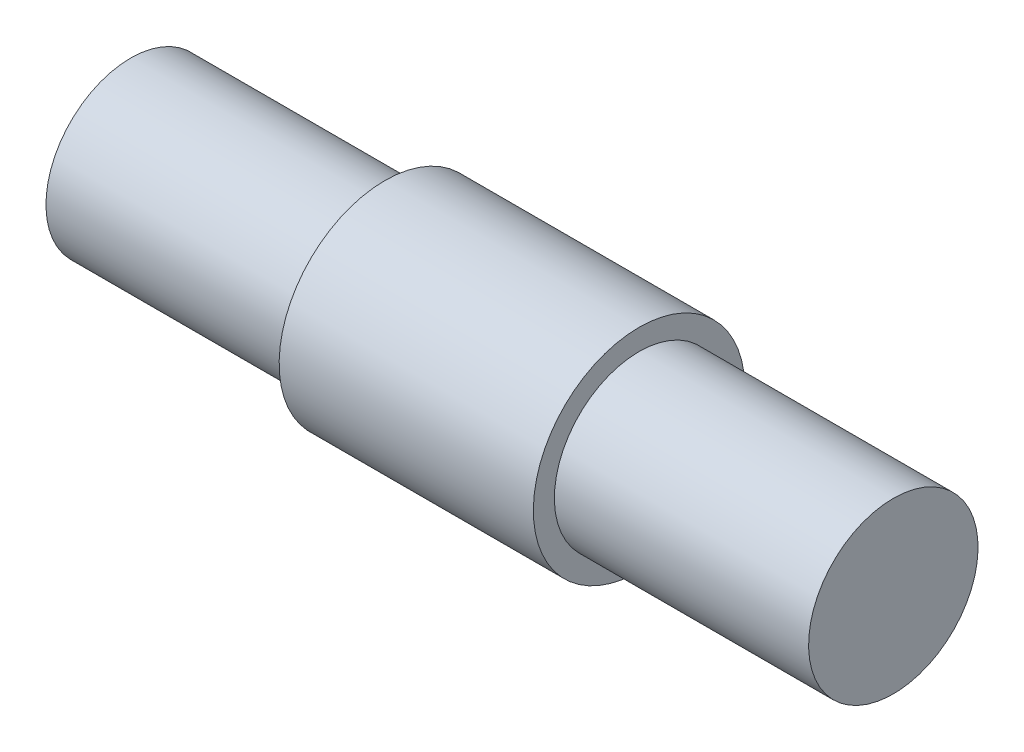
SolidWorks part; units mm, degrees
ref_plane "Front Plane" through (0, 0, 0) normal (0, 0, 1) x (1, 0, 0)
ref_plane "Top Plane" through (0, 0, 0) normal (0, 1, 0) x (1, 0, 0)
ref_plane "Right Plane" through (0, 0, 0) normal (1, 0, 0) x (0, 0, -1)
sketch "Sketch1" plane through (0, 0, 0) normal (0, 0, 1) x (1, 0, 0)
  line L0 (0, 0) -> (0, 3.9624)
  line L1 (-4.7625, 0) -> (4.7625, 0)
  line L2 (-4.7625, 3.9624) -> (4.7625, 3.9624)
  line L3 (4.7625, 0) -> (4.7625, 3.9624)
  line L4 (4.7625, 0) -> (4.7625, 3.175)
  line L5 (4.7625, 0) -> (14.2875, 0)
  line L6 (4.7625, 3.175) -> (14.2875, 3.175)
  line L7 (14.2875, 0) -> (14.2875, 3.175)
  line L8 (-4.7625, 0) -> (-14.2875, 0)
  line L9 (-14.2875, 0) -> (-14.2875, 3.175)
  line L10 (-4.7625, 3.175) -> (-14.2875, 3.175)
  line L11 (-4.7625, 0) -> (-4.7625, 3.9624)
  dimension "D1" = 4.7625
  dimension "D2" = 28.575
  dimension "D3" = 3.9624
  dimension "D4" = 3.175
  dimension "D5" = 14.2875
revolve "Revolve1" add sketch "Sketch1" angle 360 about L8
